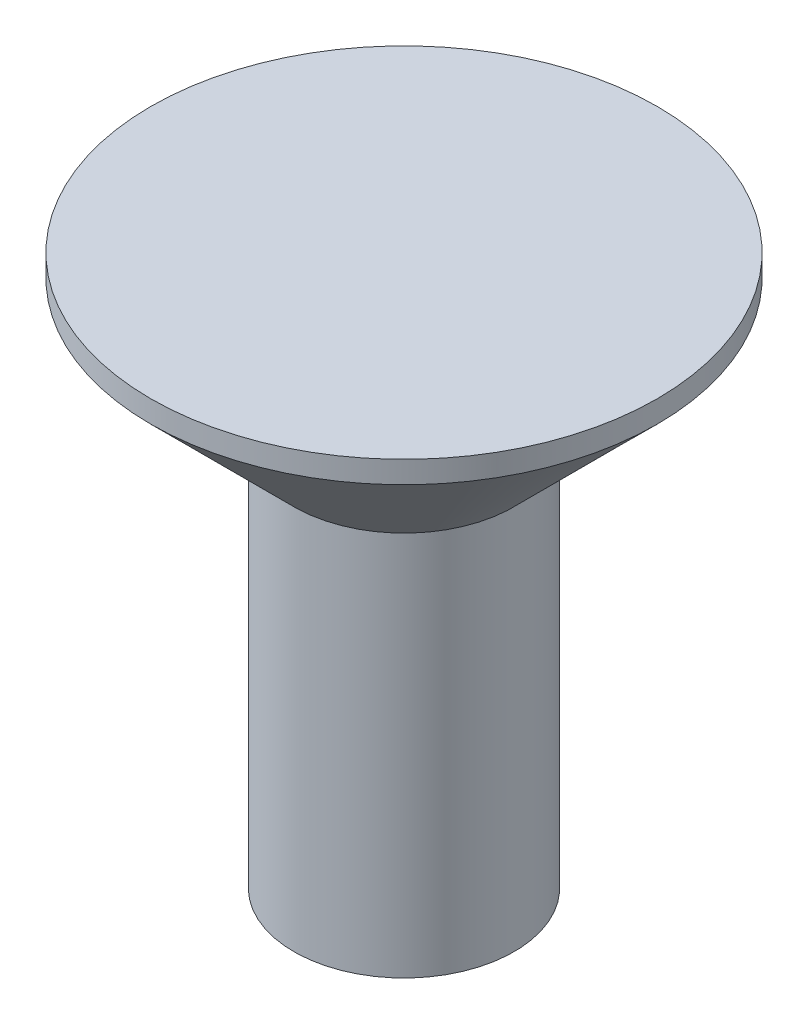
SolidWorks part; units mm, degrees
ref_plane "Front Plane" through (0, 0, 0) normal (0, 0, 1) x (1, 0, 0)
ref_plane "Top Plane" through (0, 0, 0) normal (0, 1, 0) x (1, 0, 0)
ref_plane "Right Plane" through (0, 0, 0) normal (1, 0, 0) x (0, 0, -1)
sketch "Sketch1" plane through (0, 0, 0) normal (0, 0, 1) x (1, 0, 0)
  line L0 (0, 0) -> (12.7, 0)
  line L1 (12.7, 0) -> (12.7, 44.45)
  line L2 (12.7, 44.45) -> (29.21, 60.96)
  line L3 (29.21, 63.5) -> (0, 63.5)
  line L4 (0, 63.5) -> (0, 0)
  line L5 (29.21, 63.5) -> (29.21, 60.96)
  dimension "D1" = 19.05
  dimension "D2" = 45
  dimension "D3" = 12.7
  dimension "D4" = 63.5
  dimension "D5" = 29.21
revolve "Revolve1" add sketch "Sketch1" angle 360 about L4
